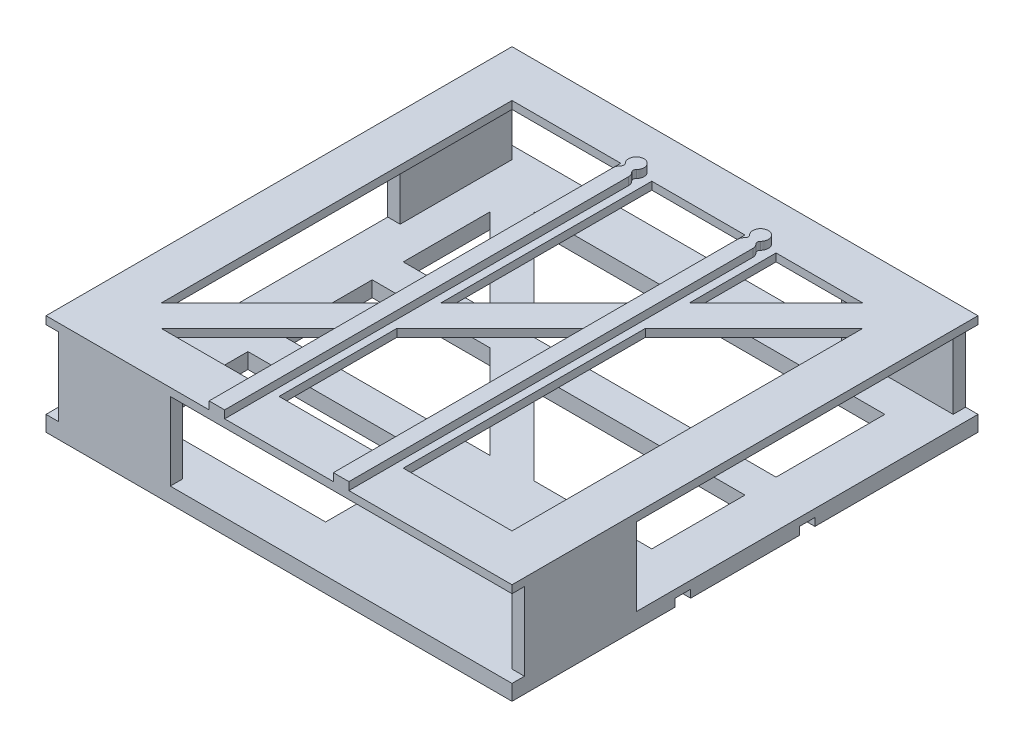
SolidWorks part; units mm, degrees
other "相机1"
material "3.0526 (EN-AW 3005)"
ref_plane "前视基准面" through (0, 0, 0) normal (0, 0, 1) x (1, 0, 0)
ref_plane "上视基准面" through (0, 0, 0) normal (0, 1, 0) x (1, 0, 0)
ref_plane "右视基准面" through (0, 0, 0) normal (1, 0, 0) x (0, 0, -1)
sketch "草图1" plane through (0, 0, 0) normal (0, 1, 0) x (1, 0, 0)
  line L0 (-15.8579, 30) -> (120, 30)
  line L1 (-150, 150) -> (150, 150)
  line L2 (-150, 150) -> (-150, -150)
  line L3 (-150, -150) -> (0, -150)
  line L4 (150, 150) -> (150, -30)
  line L5 (-105.8579, 120) -> (120, 120)
  line L6 (-120, 105.8579) -> (-120, 50)
  line L7 (-120, -120) -> (0, -120)
  line L8 (120, 120) -> (120, 50)
  line L9 (150, -150) -> (0, -150)
  line L10 (150, -150) -> (150, -30)
  line L11 (120, 30) -> (120, -30)
  line L12 (0, -120) -> (0, -50)
  line L13 (-120, 105.8579) -> (-64.1421, 50)
  line L14 (-105.8579, 120) -> (-35.8579, 50)
  line L16 (-120, -50) -> (-120, -120)
  line L17 (-120, 30) -> (-44.1421, 30)
  line L18 (-120, 50) -> (-64.1421, 50)
  line L19 (-120, -50) -> (0, -50)
  line L20 (-120, -30) -> (15.8579, -30)
  line L21 (-120, 30) -> (-120, -30)
  line L22 (44.1421, -30) -> (120, -30)
  line L26 (-44.1421, 30) -> (15.8579, -30)
  line L27 (-15.8579, 30) -> (44.1421, -30)
  line L28 (-35.8579, 50) -> (120, 50)
  point P4 (-120, 120)
  point P5 (120, -120)
  point P11 (-127.0711, 112.9289)
  point P12 (112.9289, -127.0711)
  point P13 (-112.9289, 127.0711)
  point P14 (127.0711, -112.9289)
  point P15 (-120, 40)
  point P16 (120, 40)
  point P17 (-120, -40)
  point P18 (120, -40)
  point P24 (120, -50)
extrude "凸台-拉伸1" add sketch "草图1" along normal blind 5
sketch "草图2" plane through (0, 0, 0) normal (0, -1, 0) x (1, 0, 0)
  line L0 (150, 45) -> (150, 150)
  line L5 (-110, -45) -> (150, -45)
  line L6 (-110, 35) -> (150, 35)
  line L7 (-110, -35) -> (150, -35)
  line L8 (-110, 45) -> (150, 45)
  line L9 (150, 150) -> (-150, 150)
  line L10 (-150, 150) -> (-150, -150)
  line L11 (-150, -150) -> (150, -150)
  line L12 (150, -150) -> (150, -45)
  line L13 (150, -35) -> (150, 35)
  line L14 (-120, 120) -> (-120, 50)
  line L15 (-120, 50) -> (0, 50)
  line L16 (0, 50) -> (0, 120)
  line L17 (0, 120) -> (-120, 120)
  line L18 (-120, 30) -> (-120, -30)
  line L19 (-120, -30) -> (-44.1421, -30)
  line L20 (-44.1421, -30) -> (15.8579, 30)
  line L21 (15.8579, 30) -> (-120, 30)
  line L22 (44.1421, 30) -> (-15.8579, -30)
  line L23 (-15.8579, -30) -> (120, -30)
  line L24 (120, -30) -> (120, 30)
  line L25 (120, 30) -> (44.1421, 30)
  line L26 (-120, -50) -> (-120, -105.8579)
  line L27 (-120, -105.8579) -> (-64.1421, -50)
  line L28 (-64.1421, -50) -> (-120, -50)
  line L29 (-35.8579, -50) -> (-105.8579, -120)
  line L30 (-105.8579, -120) -> (120, -120)
  line L31 (120, -120) -> (120, -50)
  line L32 (120, -50) -> (-35.8579, -50)
  arc A0 (-116.4645, 43.5355) -> (-116.4645, 36.4645) centre (-120, 40) ccw
  arc A1 (-116.4645, 43.5355) -> (-113.5355, 43.5355) centre (-115, 45) ccw
  arc A2 (-113.5355, 36.4645) -> (-116.4645, 36.4645) centre (-115, 35) ccw
  arc A3 (-110, 35) -> (-113.5355, 36.4645) centre (-110, 40) cw
  arc A4 (-113.5355, 43.5355) -> (-110, 45) centre (-110, 40) cw
  arc A5 (-113.5355, -43.5355) -> (-110, -45) centre (-110, -40) ccw
  arc A6 (-116.4645, -43.5355) -> (-113.5355, -43.5355) centre (-115, -45) cw
  arc A7 (-116.4645, -43.5355) -> (-116.4645, -36.4645) centre (-120, -40) cw
  arc A8 (-113.5355, -36.4645) -> (-116.4645, -36.4645) centre (-115, -35) cw
  arc A9 (-110, -35) -> (-113.5355, -36.4645) centre (-110, -40) ccw
  point P5 (-150, 40)
  point P8 (150, 40)
  point P11 (-120, 35)
  point P14 (-120, 45)
extrude "凸台-拉伸2" add sketch "草图2" along normal blind 5
sketch "草图3" plane through (0, 5, 0) normal (0, 1, 0) x (1, 0, 0)
  line L0 (142, -142) -> (150, -142)
  line L1 (-142, -142) -> (-70, -142)
  line L2 (150, -142) -> (150, -70)
  line L3 (150, -70) -> (142, -70)
  line L4 (142, -142) -> (142, -70)
  line L5 (-70, -150) -> (-70, -142)
  line L6 (-142, -142) -> (-142, -150)
  line L7 (-142, -150) -> (-70, -150)
  line L8 (-142, 142) -> (-142, 70)
  line L9 (-150, 70) -> (-142, 70)
  line L10 (-142, 142) -> (-150, 142)
  line L11 (-150, 142) -> (-150, 70)
  line L12 (142, 142) -> (70, 142)
  line L13 (70, 150) -> (70, 142)
  line L14 (142, 142) -> (142, 150)
  line L15 (142, 150) -> (70, 150)
  point P19 (0, 0)
  dimension "D1" = 4
extrude "凸台-拉伸3" add sketch "草图3" along normal blind 50
sketch "草图4" plane through (0, 55, 0) normal (0, 1, 0) x (1, 0, 0)
  line L0 (30, 120) -> (-30, 120)
  line L1 (-150, 150) -> (150, 150)
  line L2 (-150, 150) -> (-150, -150)
  line L3 (-150, -150) -> (150, -150)
  line L4 (150, 150) -> (150, -150)
  line L5 (105.8579, 120) -> (50, 120)
  line L6 (120, 105.8579) -> (120, -120)
  line L7 (120, -120) -> (50, -120)
  line L8 (-120, 120) -> (-120, -105.8579)
  line L9 (105.8579, 120) -> (50, 64.1421)
  line L10 (120, 105.8579) -> (50, 35.8579)
  line L11 (-50, -120) -> (-105.8579, -120)
  line L12 (30, -120) -> (-30, -120)
  line L13 (-50, 120) -> (-50, -35.8579)
  line L14 (-30, 120) -> (-30, -15.8579)
  line L15 (30, 120) -> (30, 44.1421)
  line L16 (50, 120) -> (50, 64.1421)
  line L17 (-50, 120) -> (-120, 120)
  line L18 (-50, -35.8579) -> (-120, -105.8579)
  line L19 (-30, -44.1421) -> (-30, -120)
  line L20 (-50, -64.1421) -> (-105.8579, -120)
  line L22 (-50, -64.1421) -> (-50, -120)
  line L24 (30, 15.8579) -> (30, -120)
  line L25 (30, 44.1421) -> (-30, -15.8579)
  line L27 (50, 35.8579) -> (50, -120)
  line L28 (30, 15.8579) -> (-30, -44.1421)
  point P6 (120, 120)
  point P7 (-120, -120)
  point P12 (112.9289, 127.0711)
  point P13 (-127.0711, -112.9289)
  point P14 (127.0711, 112.9289)
  point P15 (-112.9289, -127.0711)
  point P16 (-40, 120)
  point P17 (-40, -120)
  point P18 (40, 120)
  point P19 (40, -120)
extrude "凸台-拉伸4" add sketch "草图4" along normal blind 5
sketch "草图5" plane through (0, 60, 0) normal (0, 1, 0) x (1, 0, 0)
  line L0 (35, 110) -> (35, -150)
  line L1 (-45, -150) -> (-35, -150)
  line L2 (45, 110) -> (45, -150)
  line L4 (35, -150) -> (45, -150)
  line L5 (-45, 110) -> (-45, -150)
  line L6 (-35, 110) -> (-35, -150)
  arc A0 (-36.4645, 116.4645) -> (-43.5355, 116.4645) centre (-40, 120) ccw
  arc A1 (-36.4645, 116.4645) -> (-36.4645, 113.5355) centre (-35, 115) ccw
  arc A2 (-43.5355, 113.5355) -> (-43.5355, 116.4645) centre (-45, 115) ccw
  arc A3 (43.5355, 116.4645) -> (36.4645, 116.4645) centre (40, 120) ccw
  arc A4 (43.5355, 116.4645) -> (43.5355, 113.5355) centre (45, 115) ccw
  arc A5 (36.4645, 113.5355) -> (36.4645, 116.4645) centre (35, 115) ccw
  arc A6 (-36.4645, 113.5355) -> (-35, 110) centre (-40, 110) cw
  arc A7 (43.5355, 113.5355) -> (45, 110) centre (40, 110) cw
  arc A8 (-45, 110) -> (-43.5355, 113.5355) centre (-40, 110) cw
  arc A9 (35, 110) -> (36.4645, 113.5355) centre (40, 110) cw
  point P9 (-40, -150)
  point P14 (-45, 120)
  point P16 (-35, 120)
  point P18 (35, 120)
  point P20 (45, 120)
extrude "凸台-拉伸5" add sketch "草图5" along normal blind 5
